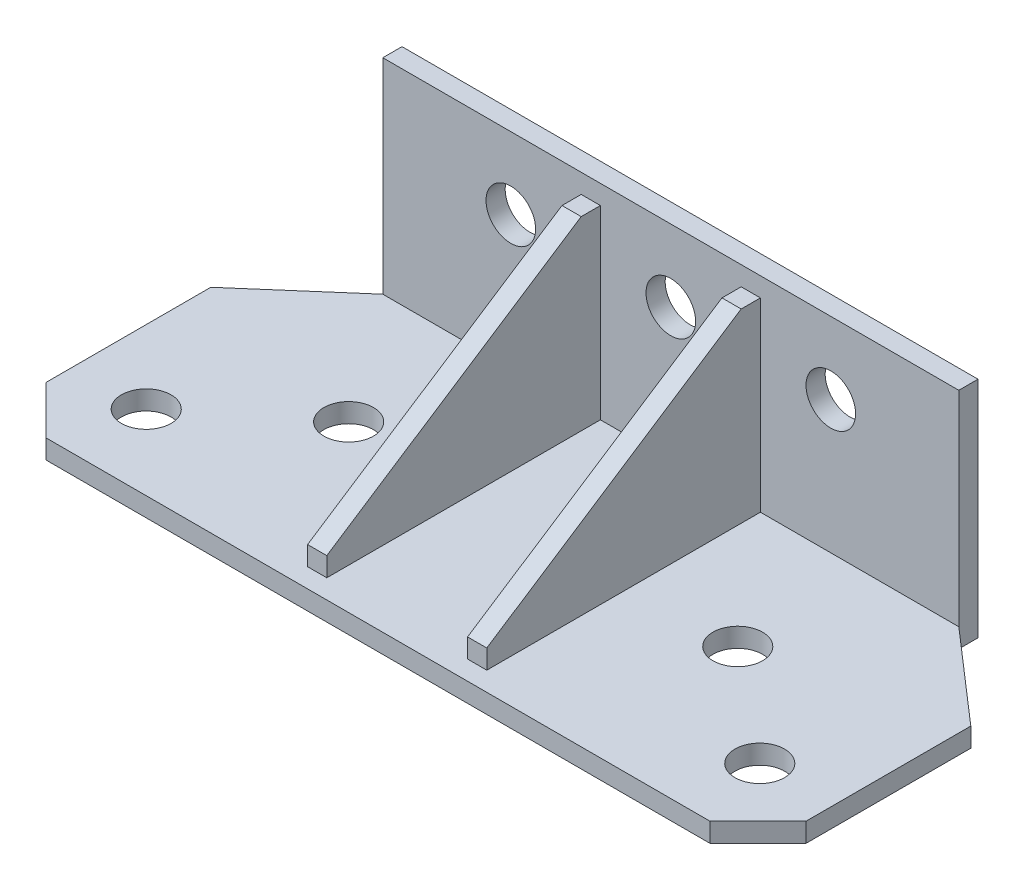
SolidWorks part; units mm, degrees
ref_plane "Front Plane" through (0, 0, 0) normal (0, 0, 1) x (1, 0, 0)
ref_plane "Top Plane" through (0, 0, 0) normal (0, 1, 0) x (1, 0, 0)
ref_plane "Right Plane" through (0, 0, 0) normal (1, 0, 0) x (0, 0, -1)
sketch "Sketch1" plane through (0, 0, 0) normal (0, 0, 1) x (1, 0, 0)
  line L1 (0, 0) -> (360, 0)
  line L2 (0, 0) -> (0, 140)
  line L3 (0, 140) -> (360, 140)
  line L4 (360, 0) -> (360, 140)
  circle A0 centre (80, 95) radius 15.5
  circle A1 centre (180, 95) radius 15.5
  circle A2 centre (280, 95) radius 15.5
  dimension "D3" = 31
  dimension "D6" = 31
  dimension "D7" = 31
  dimension "D1" = 140
  dimension "D2" = 360
  dimension "D4" = 95
  dimension "D5" = 80
  dimension "D8" = 100
  dimension "D9" = 100
  dimension "D10" = 95
  dimension "D11" = 95
extrude "Extrude1" add sketch "Sketch1" along normal blind 12
sketch "Sketch2" plane through (0, 0, 12) normal (0, 0, 1) x (1, 0, 0)
  line L0 (0, 140) -> (0, 0) construction
  line L1 (-57.5, 12) -> (417.5, 12)
  line L2 (-57.5, 12) -> (-57.5, 0)
  line L3 (-57.5, 0) -> (417.5, 0)
  line L4 (417.5, 12) -> (417.5, 0)
  line L5 (360, 0) -> (360, 140) construction
  line L6 (360, 140) -> (0, 140) construction
  dimension "D1" = 12
  dimension "D2" = 57.5
  dimension "D3" = 57.5
  dimension "D4" = 475
  dimension "D5" = 128
extrude "Extrude2" add sketch "Sketch2" along normal blind 183
sketch "Sketch3" plane through (0, 12, 0) normal (0, 1, 0) x (1, 0, 0)
  line L0 (-57.5, -195) -> (-27.5, -195)
  line L1 (417.5, -195) -> (-57.5, -195) construction
  line L2 (-27.5, -195) -> (-57.5, -165)
  line L3 (-57.5, -195) -> (-57.5, -12) construction
  line L4 (-57.5, -165) -> (-57.5, -195)
  line L5 (180, -12) -> (180, -195) construction
  line L6 (360, -12) -> (0, -12) construction
  line L7 (-57.5, -12) -> (-57.5, -62)
  line L8 (-57.5, -62) -> (0, -12)
  line L9 (0, -12) -> (-57.5, -12)
  line L10 (360, 0) -> (0, 0) construction
  line L11 (417.5, -165) -> (417.5, -195)
  line L12 (387.5, -195) -> (417.5, -165)
  line L13 (417.5, -12) -> (417.5, -62)
  line L14 (360, -12) -> (417.5, -12)
  line L15 (417.5, -62) -> (360, -12)
  line L16 (180, 6) -> (180, -1994) construction
  line L17 (180, -1994) -> (2668, -1994) construction
  line L18 (2668, -1994) -> (180, 6) construction
  circle A0 centre (301.5863, -91.7382) radius 15.5
  circle A1 centre (371.7323, -148.1257) radius 15.5
  circle A2 centre (58.4137, -91.7382) radius 15.5
  circle A3 centre (-11.7323, -148.1257) radius 15.5
  line M1 (417.5, -12) -> (360, -12)
  line M3 (0, -12) -> (-57.5, -12)
  line M4 (-57.5, -12) -> (-57.5, -195)
  line M5 (-57.5, -195) -> (417.5, -195)
  line M6 (417.5, -195) -> (417.5, -12)
  dimension "D7" = 31
  dimension "D9" = 31
  dimension "D1" = 30
  dimension "D2" = 30
  dimension "D3" = 62
  dimension "D4" = 2488
  dimension "D5" = 2000
  dimension "D6" = 6
  dimension "D8" = 156
  dimension "D10" = 90
extrude "Extrude3" cut sketch "Sketch3" against normal blind 183 contours L15 M6 M1 | L12 M5 M6 | L2 M5 M4 | L8 M4 M3 | A2 | A3 | A0 | A1
sketch "Sketch4" plane through (0, 0, 12) normal (0, 0, 1) x (1, 0, 0)
  line L0 (387.5, 12) -> (-27.5, 12) construction
  line L1 (124, 128) -> (136, 128)
  line L2 (124, 128) -> (124, 12)
  line L3 (124, 12) -> (136, 12)
  line L4 (136, 128) -> (136, 12)
  line L5 (180, 140) -> (180, 12) construction
  line L6 (360, 140) -> (0, 140) construction
  line L7 (236, 128) -> (224, 128)
  line L8 (224, 128) -> (224, 12)
  line L9 (236, 12) -> (224, 12)
  line L10 (236, 128) -> (236, 12)
  dimension "D1" = 12
  dimension "D2" = 12
  dimension "D3" = 44
extrude "Extrude4" add sketch "Sketch4" along normal blind 171
sketch "Sketch5" plane through (124, 0, 0) normal (-1, 0, 0) x (0, 0, 1)
  line L0 (183, 128) -> (183, 24)
  line L1 (183, 128) -> (183, 12) construction
  line L2 (183, 24) -> (24, 128)
  line L3 (183, 128) -> (12, 128) construction
  line L4 (24, 128) -> (183, 128)
  line L5 (12, 140) -> (12, 12) construction
  dimension "D1" = 12
  dimension "D2" = 12
extrude "Extrude5" cut sketch "Sketch5" against normal blind 183
